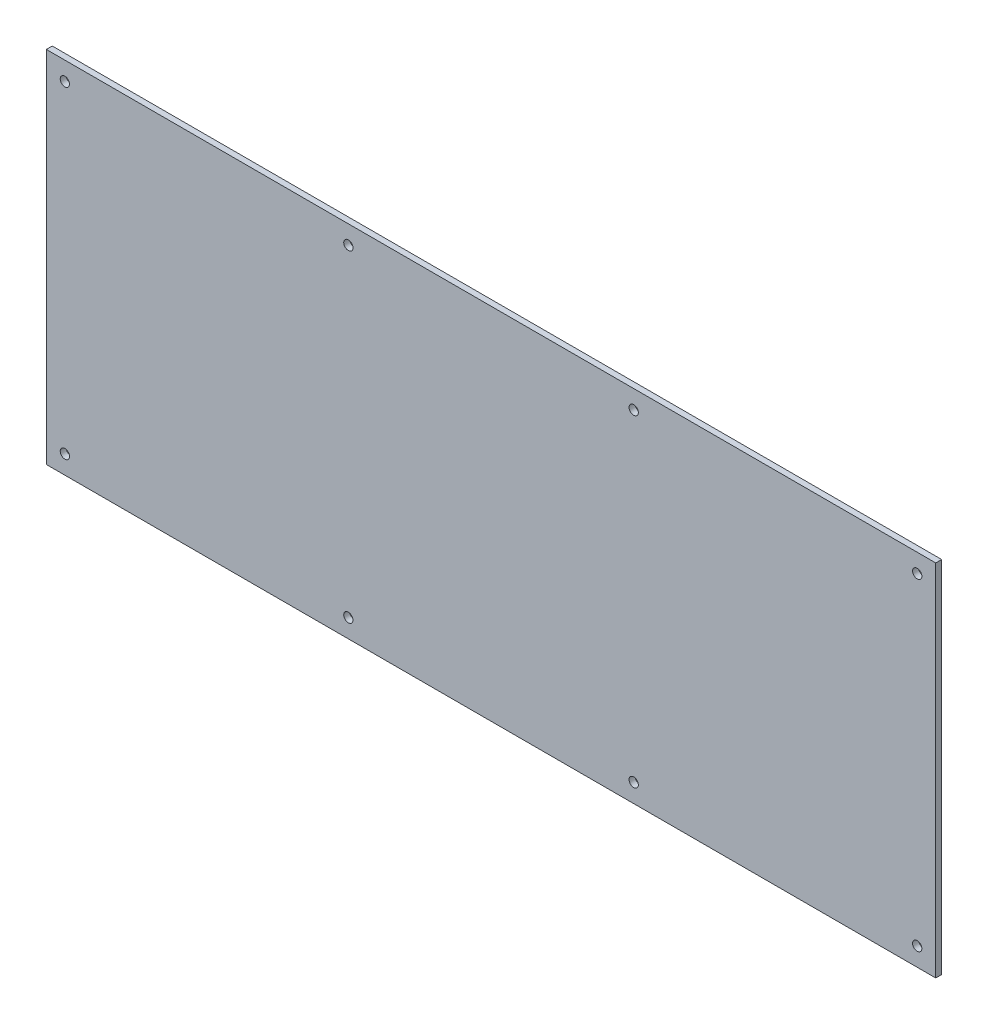
SolidWorks part; units mm, degrees
material "Acrylic (Medium-high impact)"
ref_plane "Front Plane" through (0, 0, 0) normal (0, 0, 1) x (1, 0, 0)
ref_plane "Top Plane" through (0, 0, 0) normal (0, 1, 0) x (1, 0, 0)
ref_plane "Right Plane" through (0, 0, 0) normal (1, 0, 0) x (0, 0, -1)
sketch "Sketch1" plane through (0, 0, 0) normal (0, 0, 1) x (1, 0, 0)
  line L1 (0, 123.19) -> (304.8, 123.19)
  line L2 (0, 123.19) -> (0, 0)
  line L3 (0, 0) -> (304.8, 0)
  line L4 (304.8, 123.19) -> (304.8, 0)
  line L5 (304.8, 142.24) -> (0, 142.24) construction
  dimension "D1" = 19.05
extrude "Extrude1" add sketch "Sketch1" along normal blind 2.032
sketch "Sketch2" plane through (0, 0, 2.032) normal (0, 0, 1) x (1, 0, 0)
  line L0 (6.35, 135.89) -> (6.35, -13.3686) construction
  line L1 (103.505, 135.89) -> (103.505, -17.3004) construction
  line L2 (152.4, 142.24) -> (152.4, -27.4441) construction
  line L5 (304.8, 116.84) -> (0, 116.84)
  line L6 (304.8, 116.84) -> (25.4, 116.84) construction
  circle A0 centre (6.35, 116.84) radius 1.5875
  circle A1 centre (6.35, 6.35) radius 1.5875 construction
  circle A2 centre (6.35, 6.35) radius 1.5875
  circle A3 centre (103.505, 6.35) radius 1.5875 construction
  circle A4 centre (103.505, 6.35) radius 1.5875
  circle A5 centre (103.505, 116.84) radius 1.5875
  circle A6 centre (201.295, 116.84) radius 1.5875
  circle A7 centre (201.295, 6.35) radius 1.5875
  circle A8 centre (298.45, 6.35) radius 1.5875
  circle A9 centre (298.45, 116.84) radius 1.5875
  dimension "D1" = 6.35
extrude "Cut-Extrude1" cut sketch "Sketch2" against normal through all
